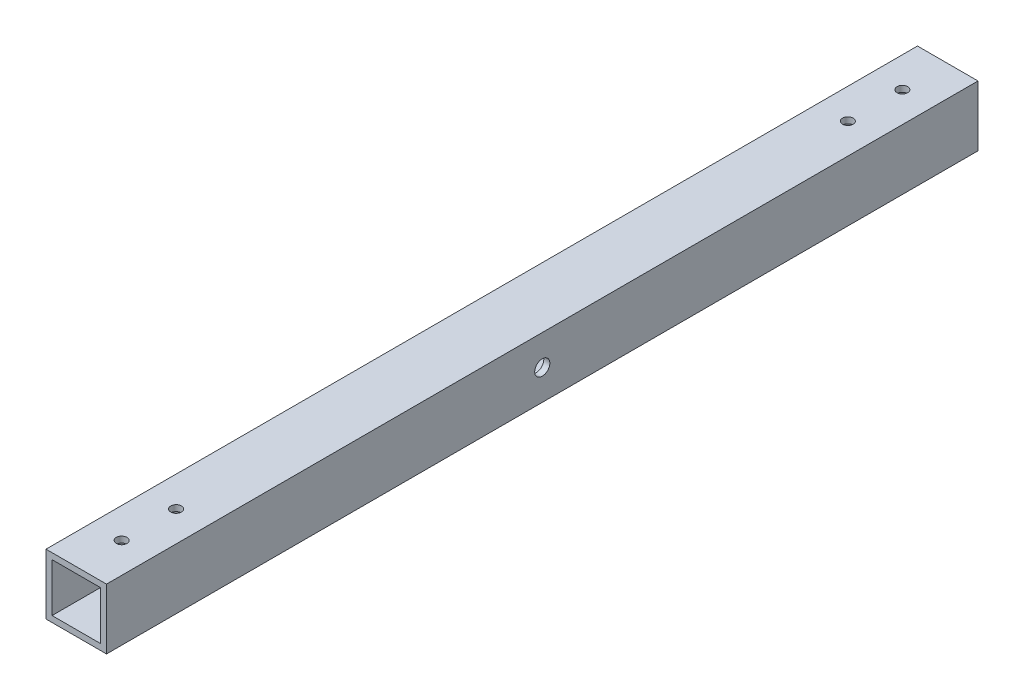
SolidWorks part; units mm, degrees
ref_plane "Front Plane" through (0, 0, 0) normal (0, 0, 1) x (1, 0, 0)
ref_plane "Top Plane" through (0, 0, 0) normal (0, 1, 0) x (1, 0, 0)
ref_plane "Right Plane" through (0, 0, 0) normal (1, 0, 0) x (0, 0, -1)
sketch "Sketch1" plane through (0, 0, 0) normal (0, 0, 1) x (1, 0, 0)
  line L0 (31.75, 0) -> (25.4, 0) construction
  line L1 (-31.75, 0) -> (31.75, 0) construction
  line L2 (0, 31.75) -> (0, -31.75)
  point P7 (0, 0)
sketch "Sketch2" plane through (0, 0, 0) normal (1, 0, 0) x (0, 0, -1)
  line L0 (457.2, 0) -> (-457.2, 0)
  point P4 (0, 0)
  dimension "Length" = 914.4
sketch "Sketch3" plane through (0, 0, 0) normal (0, 0, 1) x (1, 0, 0)
  line L0 (-31.75, 0) -> (31.75, 0) construction
  line L5 (31.75, -31.75) -> (-31.75, -31.75)
  line L6 (31.75, -31.75) -> (31.75, 31.75)
  line L11 (31.75, 31.75) -> (-31.75, 31.75)
  line L12 (-31.75, -31.75) -> (-31.75, 31.75)
  line L14 (31.75, -31.75) -> (-31.75, 31.75) construction
  line L15 (31.75, 31.75) -> (-31.75, -31.75) construction
  line L16 (25.4, -25.4) -> (-25.4, -25.4)
  line L17 (25.4, -25.4) -> (25.4, 25.4)
  line L18 (25.4, 25.4) -> (-25.4, 25.4)
  line L19 (-25.4, -25.4) -> (-25.4, 25.4)
  line L20 (25.4, -25.4) -> (-25.4, 25.4) construction
  line L21 (25.4, 25.4) -> (-25.4, -25.4) construction
  point P0 (0, 0)
  point P5 (0, 0)
  point P13 (25.4, -31.75)
  dimension "D1" = 6.35
  dimension "D3" = 63.5
  dimension "D4" = 63.5
  dimension "D2" = 6.35
extrude "Boss-Extrude1" add sketch "Sketch3" along normal up to vertex (457.2 mm away) and the other way up to vertex (457.2 mm away) up to point (0, 0, 457.2) other way up to point (0, 0, -457.2)
sketch "Sketch5" plane through (0, 0, 0) normal (1, 0, 0) x (0, 0, -1)
  line L0 (-457.2, 0) -> (457.2, 0) construction
  line L3 (-457.2, -31.75) -> (-457.2, 31.75) construction
  line L4 (457.2, -31.75) -> (457.2, 31.75) construction
  point P6 (-385.7625, 0)
  point P7 (-361.95, 0)
  point P8 (361.95, 0)
  point P10 (385.7625, 0)
  dimension "D1" = 71.4375
  dimension "D2" = 95.25
  dimension "D3" = 71.4375
  dimension "D4" = 95.25
sketch "Sketch6" plane through (0, 31.75, 0) normal (0, 1, 0) x (1, 0, 0)
  line L0 (0, 457.2) -> (0, 388.9644) construction
  line L1 (31.75, 457.2) -> (-31.75, 457.2) construction
  line L2 (31.75, -457.2) -> (-31.75, -457.2) construction
  line L3 (0, -457.2) -> (0, -352.425) construction
  circle A0 centre (0, 409.575) radius 5.588
  circle A1 centre (0, -409.575) radius 5.588
  circle A2 centre (0, -352.425) radius 5.588
  circle A3 centre (0, 352.425) radius 5.588
  point P16 (0, -354.1588)
  point P17 (0, 0)
  dimension "D5" = 11.176
  dimension "D6" = 11.176
  dimension "D7" = 11.176
  dimension "D8" = 11.176
  dimension "D1" = 47.625
  dimension "D2" = 47.625
  dimension "D3" = 57.15
  dimension "D4" = 57.15
extrude "Cut-Extrude1" cut sketch "Sketch6" against normal through all
sketch "Sketch7" plane through (31.75, 0, 0) normal (1, 0, 0) x (0, 0, -1)
  line L1 (-457.2, -31.75) -> (457.2, -31.75) construction
  line L2 (-457.2, -31.75) -> (-457.2, 31.75) construction
  line L3 (-457.2, 31.75) -> (457.2, 31.75) construction
  line L4 (457.2, -31.75) -> (457.2, 31.75) construction
  line L5 (-457.2, -31.75) -> (457.2, 31.75) construction
  line L6 (-457.2, 31.75) -> (457.2, -31.75) construction
  circle A0 centre (0, 0) radius 7.9375
  point P0 (0, 0)
  dimension "D1" = 15.875
extrude "Cut-Extrude2" cut sketch "Sketch7" against normal through all
sketch "Sketch9" plane through (0, 31.75, 0) normal (0, 1, 0) x (1, 0, 0)
  line L0 (0, 0) -> (0, 203.2)
  point P4 (0, 0)
  point P5 (0, 203.2)
  point P6 (0, 229.7234)
  dimension "D1" = 203.2
equation "\"D1@Sketch3\"=\"Wall thickness@Sketch1\""
equation "\"D1@Sketch5\"=\"Width@Sketch1\"*1.125"
equation "\"D2@Sketch5\"=\"Width@Sketch1\"*1.5"
equation "\"D3@Sketch5\"=\"D1@Sketch5\""
equation "\"D4@Sketch5\"=\"D2@Sketch5\""
equation "\"D2@Sketch3\"=\"Wall Thickness@Sketch1\""
